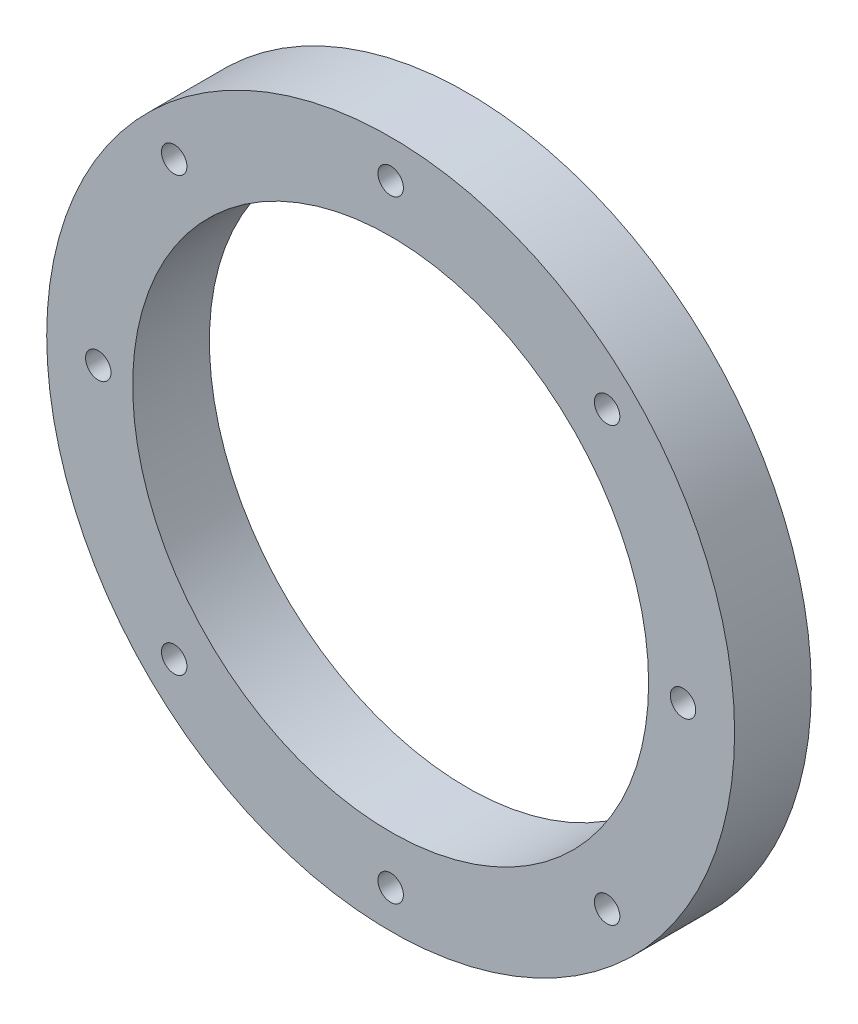
SolidWorks part; units mm, degrees
ref_plane "前视基准面" through (0, 0, 0) normal (0, 0, 1) x (1, 0, 0)
ref_plane "上视基准面" through (0, 0, 0) normal (0, 1, 0) x (1, 0, 0)
ref_plane "右视基准面" through (0, 0, 0) normal (1, 0, 0) x (0, 0, -1)
other "Configuration Table"
sketch "草图1" plane through (0, 0, 0) normal (0, 0, 1) x (1, 0, 0)
  circle A10 centre (0, 0) radius 50
  circle A11 centre (0, 0) radius 37.5
  circle A12 centre (42.5, 0) radius 1.85
  circle A13 centre (-42.5, 0) radius 1.85
  circle A14 centre (0, 44.5) radius 1.85
  circle A15 centre (31.4663, 31.4663) radius 1.85
  circle A16 centre (44.5, 0) radius 1.85
  circle A17 centre (31.4663, -31.4663) radius 1.85
  circle A18 centre (0, -44.5) radius 1.85
  circle A19 centre (-31.4663, -31.4663) radius 1.85
  circle A20 centre (-44.5, 0) radius 1.85
  circle A21 centre (-31.4663, 31.4663) radius 1.85
  point P9 (0, 0)
  point P27 (0, 0)
  dimension "D1" = 100
  dimension "D2" = 75
  dimension "D3" = 3.7
  dimension "D4" = 42.5
  dimension "D6" = 3.7
  dimension "D7" = 44.5
  dimension "D5" = 2
  dimension "D8" = 8
extrude "凸台-拉伸1" add sketch "草图1" along normal blind 11.15 contours A10 A21 A20 A13 A19 A18 A17 A16 A12 A15 A14 A11 | A12 A16 | A13 A20
